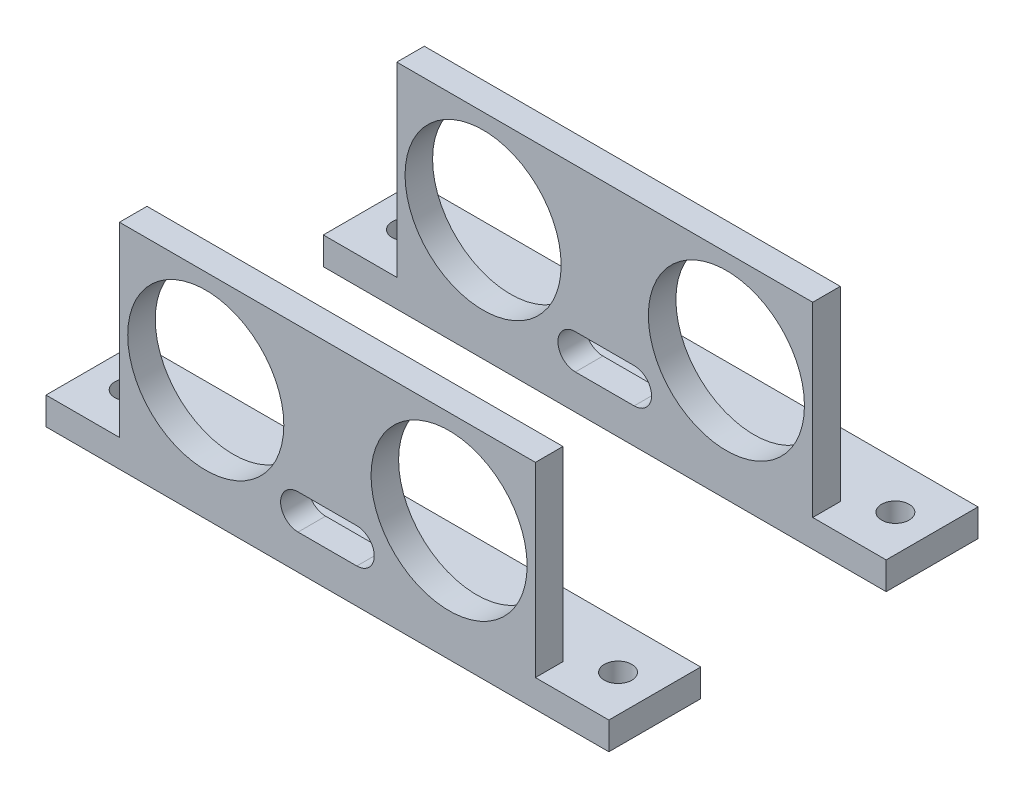
SolidWorks part; units mm, degrees
ref_plane "Front Plane" through (0, 0, 0) normal (0, 0, 1) x (1, 0, 0)
ref_plane "Top Plane" through (0, 0, 0) normal (0, 1, 0) x (1, 0, 0)
ref_plane "Right Plane" through (0, 0, 0) normal (1, 0, 0) x (0, 0, -1)
sketch "Sketch1" plane through (0, 0, 0) normal (0, 0, 1) x (1, 0, 0)
  line L1 (98.6394, -11.1578) -> (-71.3606, -11.1578)
  line L2 (98.6394, -11.1578) -> (98.6394, -8.1578)
  line L3 (98.6394, -8.1578) -> (-71.3606, -8.1578)
  line L4 (-71.3606, -11.1578) -> (-71.3606, -8.1578)
  line L5 (98.6394, -11.1578) -> (-71.3606, -8.1578) construction
  line L6 (98.6394, -8.1578) -> (-71.3606, -11.1578) construction
  point P0 (13.6394, -9.6578)
extrude "Boss-Extrude1" add sketch "Sketch1" along normal blind 10
sketch "Sketch2" plane through (0, -8.1578, 0) normal (0, 1, 0) x (1, 0, 0)
  line L0 (98.6394, -10) -> (-71.3606, -10) construction
  line L1 (-53.3606, -7) -> (-8.0606, -7)
  line L2 (-53.3606, -7) -> (-53.3606, -10)
  line L3 (-53.3606, -10) -> (-8.0606, -10)
  line L4 (-8.0606, -7) -> (-8.0606, -10)
  line L5 (-53.3606, -7) -> (-8.0606, -10) construction
  line L6 (-53.3606, -10) -> (-8.0606, -7) construction
  line L7 (-71.3606, -10) -> (-71.3606, 0) construction
  point P0 (-30.7106, -8.5)
  dimension "D1" = 0
  dimension "D2" = 18
sketch "Sketch4" plane through (0, -8.1578, 0) normal (0, 1, 0) x (1, 0, 0)
  line L0 (-71.3606, -10) -> (-71.3606, 0) construction
  line L1 (98.6394, -10) -> (98.6394, 0) construction
  circle A0 centre (-63.3606, -4.9385) radius 1.2
  circle A1 centre (90.6394, -5.2832) radius 1.2
  dimension "D1" = 8
  dimension "D2" = 8
extrude "Cut-Extrude1" cut sketch "Sketch4" against normal blind 21
extrude "Boss-Extrude6" add sketch "Sketch2" along normal blind 20.3
sketch "Sketch5" plane through (0, 0, 7) normal (0, 0, -1) x (-1, 0, 0)
  line L0 (8.0606, 12.1422) -> (8.0606, -8.1578) construction
  line L1 (53.3606, 12.1422) -> (53.3606, -8.1578) construction
  line L2 (8.0606, 12.1422) -> (53.3606, 12.1422) construction
  line L3 (27.5106, -5.4578) -> (33.9106, -5.4578) construction
  line L4 (27.5106, -3.5578) -> (33.9106, -3.5578)
  line L5 (27.5106, -7.3578) -> (33.9106, -7.3578)
  circle A0 centre (17.4606, 1.9422) radius 8.5
  circle A1 centre (43.9606, 1.9422) radius 8.5
  arc A2 (27.5106, -3.5578) -> (27.5106, -7.3578) centre (27.5106, -5.4578) ccw
  arc A3 (33.9106, -7.3578) -> (33.9106, -3.5578) centre (33.9106, -5.4578) ccw
  point P12 (30.7106, -5.4578)
  dimension "D1" = 26.5
  dimension "D6" = 1.9
  dimension "D2" = 9.4
  dimension "D3" = 9.4
  dimension "D4" = 10.2
  dimension "D5" = 10.2
  dimension "D7" = 6.4
  dimension "D8" = 15.7
  dimension "D9" = 19.45
  dimension "D10" = 19.45
extrude "Cut-Extrude2" cut sketch "Sketch5" against normal blind 20.3
sketch "Sketch6" plane through (0, -8.1578, 0) normal (0, 1, 0) x (1, 0, 0)
  line L0 (98.6394, -10) -> (-8.0606, -10) construction
  line L1 (35.3394, -7) -> (80.6394, -7)
  line L2 (35.3394, -7) -> (35.3394, -10)
  line L3 (35.3394, -10) -> (80.6394, -10)
  line L4 (80.6394, -7) -> (80.6394, -10)
  line L5 (35.3394, -7) -> (80.6394, -10) construction
  line L6 (35.3394, -10) -> (80.6394, -7) construction
  line L7 (98.6394, -10) -> (98.6394, 0) construction
  point P0 (57.9894, -8.5)
  point P9 (80.6394, -8.5)
  dimension "D1" = 0
  dimension "D2" = 18
extrude "Boss-Extrude7" add sketch "Sketch6" along normal blind 20.3
sketch "Sketch7" plane through (0, 0, 10) normal (0, 0, 1) x (1, 0, 0)
  line L0 (35.3394, 12.1422) -> (35.3394, -8.1578) construction
  line L1 (35.3394, 12.1422) -> (80.6394, 12.1422) construction
  line L3 (-33.9106, -7.3578) -> (-27.5106, -7.3578) construction
  line L4 (-71.3606, -11.1578) -> (98.6394, -11.1578) construction
  line L5 (-53.3606, 12.1422) -> (-53.3606, -8.1578) construction
  line L6 (54.8394, -5.4578) -> (61.2394, -5.4578) construction
  line L7 (54.8394, -3.5578) -> (61.2394, -3.5578)
  line L8 (54.8394, -7.3578) -> (61.2394, -7.3578)
  circle A0 centre (44.7394, 1.9422) radius 8.5
  circle A1 centre (71.2394, 1.9422) radius 8.5
  circle A2 centre (-43.9606, 1.9422) radius 8.5 construction
  circle A3 centre (-17.4606, 1.9422) radius 8.5 construction
  arc A5 (-33.9106, -3.5578) -> (-33.9106, -7.3578) centre (-33.9106, -5.4578) ccw construction
  arc A6 (54.8394, -3.5578) -> (54.8394, -7.3578) centre (54.8394, -5.4578) ccw
  arc A7 (61.2394, -7.3578) -> (61.2394, -3.5578) centre (61.2394, -5.4578) ccw
  point P23 (58.0394, -5.4578)
  dimension "D1" = 26.5
  dimension "D6" = 3.8
  dimension "D7" = 19.45
  dimension "D9" = 19.5
  dimension "D10" = 1.9
  dimension "D2" = 26.5
  dimension "D3" = 9.4
  dimension "D4" = 10.2
  dimension "D5" = 10.2
  dimension "D8" = 3.8
extrude "Cut-Extrude3" cut sketch "Sketch7" against normal through all
sketch "Sketch12" plane through (0, -8.1578, 0) normal (0, 1, 0) x (1, 0, 0)
  line L0 (98.6394, -10) -> (98.6394, 0) construction
  line L1 (9.9394, 4.0024) -> (98.6394, 4.0024)
  line L2 (9.9394, 4.0024) -> (9.9394, -13.2393)
  line L3 (9.9394, -13.2393) -> (98.6394, -13.2393)
  line L4 (98.6394, 4.0024) -> (98.6394, -13.2393)
  line L5 (9.9394, 4.0024) -> (98.6394, -13.2393) construction
  line L6 (9.9394, -13.2393) -> (98.6394, 4.0024) construction
  line L7 (-8.0606, -10) -> (-8.0606, -7) construction
  point P0 (54.2894, -4.6184)
  dimension "D1" = 0
  dimension "D2" = 18
extrude "Cut-Extrude5" cut sketch "Sketch12" against normal through all both and the other way through all
sketch "Sketch13" plane through (0, -8.1578, 0) normal (0, 1, 0) x (1, 0, 0)
  line L0 (-53.3606, -7) -> (-53.3606, -10) construction
  line L1 (-90.4965, 23.215) -> (-53.3606, 23.215)
  line L2 (-90.4965, 23.215) -> (-90.4965, -15.2472)
  line L3 (-90.4965, -15.2472) -> (-53.3606, -15.2472)
  line L4 (-53.3606, 23.215) -> (-53.3606, -15.2472)
  line L5 (-90.4965, 23.215) -> (-53.3606, -15.2472) construction
  line L6 (-90.4965, -15.2472) -> (-53.3606, 23.215) construction
  line L7 (30.4015, -40.9439) -> (-8.0606, -40.9439)
  line L8 (30.4015, -40.9439) -> (30.4015, 6.8023)
  line L9 (30.4015, 6.8023) -> (-8.0606, 6.8023)
  line L10 (-8.0606, -40.9439) -> (-8.0606, 6.8023)
  line L11 (30.4015, -40.9439) -> (-8.0606, 6.8023) construction
  line L12 (30.4015, 6.8023) -> (-8.0606, -40.9439) construction
  line L13 (-8.0606, -10) -> (-8.0606, -7) construction
  point P0 (-71.9286, 3.9839)
  point P5 (11.1705, -17.0708)
  point P12 (-53.3606, -8.5)
  dimension "D1" = 0
  dimension "D2" = 0
extrude "Cut-Extrude6" cut sketch "Sketch13" against normal through all both and the other way through all
sketch "Sketch15" plane through (0, -11.1578, 0) normal (0, -1, 0) x (1, 0, 0)
  line L0 (-53.3606, 10) -> (-8.0606, 10) construction
  line L1 (-53.3606, 0) -> (-61.3606, 0)
  line L2 (-53.3606, 0) -> (-53.3606, 10)
  line L3 (-53.3606, 10) -> (-61.3606, 10)
  line L4 (-61.3606, 0) -> (-61.3606, 10)
  line L5 (-53.3606, 0) -> (-61.3606, 10) construction
  line L6 (-53.3606, 10) -> (-61.3606, 0) construction
  line L7 (-0.0606, 0) -> (-8.0606, 0)
  line L8 (-0.0606, 0) -> (-0.0606, 10)
  line L9 (-0.0606, 10) -> (-8.0606, 10)
  line L10 (-8.0606, 0) -> (-8.0606, 10)
  line L11 (-0.0606, 0) -> (-8.0606, 10) construction
  line L12 (-0.0606, 10) -> (-8.0606, 0) construction
  line L13 (-53.3606, 0) -> (-8.0606, 0) construction
  line L14 (-53.3606, 10) -> (-53.3606, 0) construction
  line L15 (-8.0606, 7) -> (-8.0606, 0) construction
  point P0 (-57.3606, 5)
  point P5 (-4.0606, 5)
  dimension "D1" = 0
  dimension "D2" = 0
  dimension "D3" = 0
  dimension "D4" = 0
  dimension "D5" = 0
  dimension "D6" = 0
extrude "Boss-Extrude9" add sketch "Sketch15" against normal blind 3
sketch "Sketch16" plane through (0, -11.1578, 0) normal (0, -1, 0) x (-1, 0, 0)
  line L0 (61.3606, -10) -> (61.3606, 0) construction
  line L1 (61.3606, 0) -> (0.0606, 0) construction
  line L2 (61.3606, -10) -> (0.0606, -10) construction
  line L3 (0.0606, 0) -> (0.0606, -10) construction
  circle A0 centre (57.3606, -5) radius 1.5
  circle A1 centre (4.0606, -5) radius 1.5
  dimension "D1" = 4
  dimension "D2" = 5
  dimension "D3" = 5
  dimension "D4" = 4
extrude "Cut-Extrude7" cut sketch "Sketch16" against normal through all both and the other way through all
move or copy body "Body-Move/Copy1" bodies to move or copy 139 copy yes number of copies 1 translate (0, 0, -30.2024) parameters "D1"=0, "D2"=0, "D3"=30.2024
